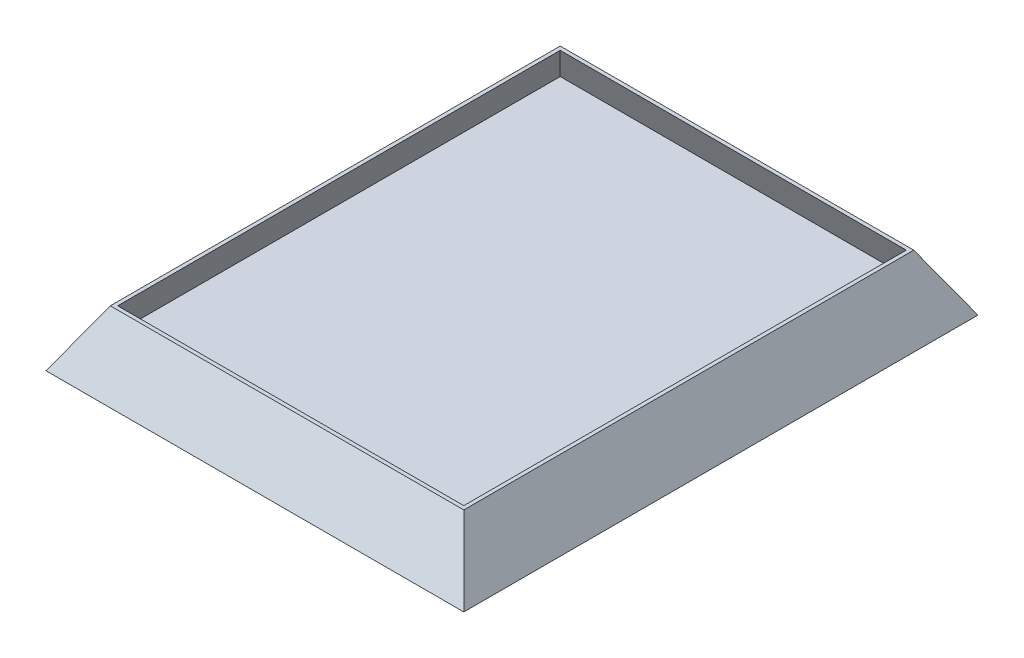
SolidWorks part; units mm, degrees
ref_plane "Front Plane" through (0, 0, 0) normal (0, 0, 1) x (1, 0, 0)
ref_plane "Top Plane" through (0, 0, 0) normal (0, 1, 0) x (1, 0, 0)
ref_plane "Right Plane" through (0, 0, 0) normal (1, 0, 0) x (0, 0, -1)
sketch "Sketch1" plane through (0, 0, 0) normal (0, 1, 0) x (1, 0, 0)
  line L1 (-279.4, -355.6) -> (279.4, -355.6)
  line L2 (-279.4, -355.6) -> (-279.4, 355.6)
  line L3 (-279.4, 355.6) -> (279.4, 355.6)
  line L4 (279.4, -355.6) -> (279.4, 355.6)
  line L5 (-279.4, -355.6) -> (279.4, 355.6) construction
  line L6 (-279.4, 355.6) -> (279.4, -355.6) construction
  point P0 (0, 0)
  dimension "D1" = 711.2
  dimension "D2" = 558.8
ref_plane "Plane1" through (0, -88.9, 0) normal (0, 1, 0) x (1, 0, 0)
sketch "Sketch2" plane through (0, -88.9, 0) normal (0, 1, 0) x (1, 0, 0)
  line L0 (279.4, -355.6) -> (279.4, 355.6) construction
  line L1 (330.2, 406.4) -> (-330.2, 406.4)
  line L2 (330.2, 406.4) -> (330.2, -406.4)
  line L3 (330.2, -406.4) -> (-330.2, -406.4)
  line L4 (-330.2, 406.4) -> (-330.2, -406.4)
  line L5 (330.2, 406.4) -> (-330.2, -406.4) construction
  line L6 (330.2, -406.4) -> (-330.2, 406.4) construction
  line L7 (-279.4, -355.6) -> (279.4, -355.6) construction
  point P0 (0, 0)
  dimension "D1" = 50.8
  dimension "D2" = 50.8
loft "Loft1" add profiles "Sketch2", "Sketch1"
shell "Shell1" thickness 5.08
